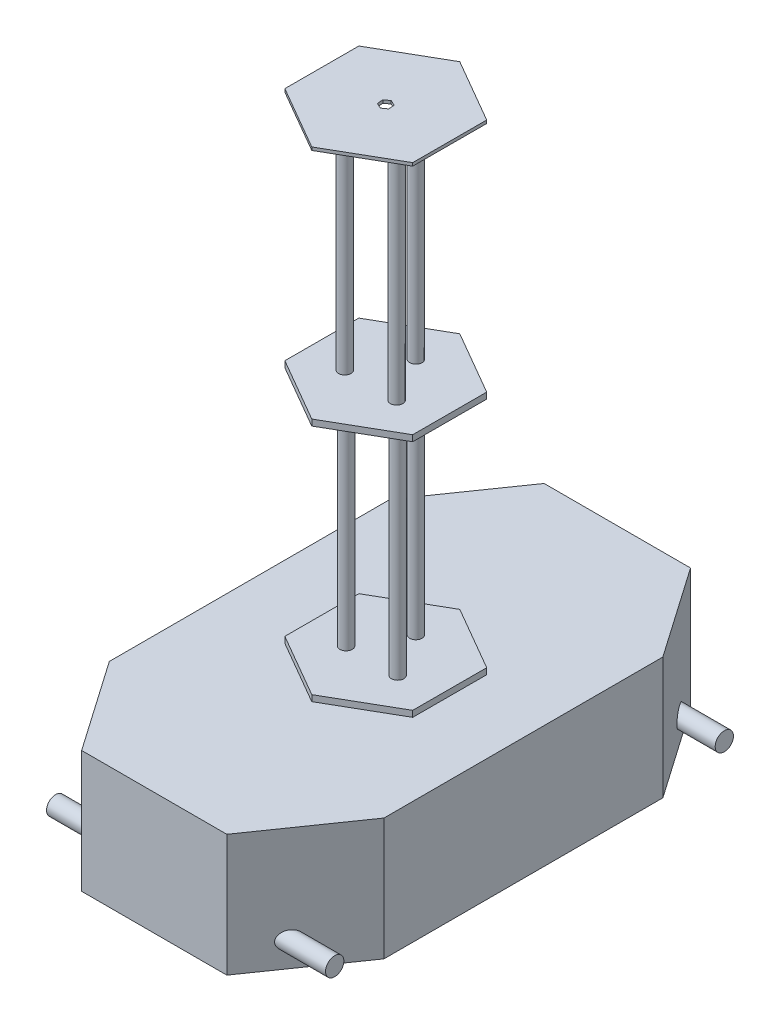
SolidWorks part; units mm, degrees
ref_plane "Front Plane" through (0, 0, 0) normal (0, 0, 1) x (1, 0, 0)
ref_plane "Top Plane" through (0, 0, 0) normal (0, 1, 0) x (1, 0, 0)
ref_plane "Right Plane" through (0, 0, 0) normal (1, 0, 0) x (0, 0, -1)
sketch "Sketch1" plane through (0, 0, 0) normal (0, 1, 0) x (1, 0, 0)
  line L0 (-1.4839, 377.6504) -> (238.5161, 377.6504)
  line L1 (-1.4839, 377.6504) -> (238.5161, 377.6504)
  line L2 (-105.1951, 228.5791) -> (-105.1951, -231.4209)
  line L3 (-1.4839, -380.4923) -> (236.539, -380.4923)
  line L4 (342.2273, 228.5791) -> (342.2273, -228.5791)
  line L12 (342.2273, 228.5791) -> (342.2273, -228.5791)
  line L14 (-1.4839, 377.6504) -> (-105.1951, 228.5791)
  line L15 (238.5161, 377.6504) -> (342.2273, 228.5791)
  line L16 (342.2273, -228.5791) -> (236.539, -380.4923)
  line L17 (-1.4839, -380.4923) -> (-105.1951, -231.4209)
  line L18 (-1.4839, 377.6504) -> (238.5161, 377.6504)
  point P0 (0, 0)
  point P1 (0, 0)
  point P2 (0, 0)
  point P9 (118.5161, 377.6504)
  point P12 (0, 0)
  dimension "D1" = 240
  dimension "D2" = 460
  dimension "D3" = 447.4224
  dimension "D4" = 758.1427
extrude "Boss-Extrude1" add sketch "Sketch1" along normal blind 200 contours L17 L3 L16 L4 L15 L0 L14 L2
sketch "Sketch2" plane through (0, 200, 0) normal (0, 1, 0) x (1, 0, 0)
  line L0 (118.5161, 377.6504) -> (117.5275, -380.4923)
  line L1 (-1.4839, 377.6504) -> (238.5161, 377.6504) construction
  line L2 (-1.4839, -380.4923) -> (236.539, -380.4923) construction
  line L3 (-105.1951, -1.4209) -> (342.2273, 0)
  line L4 (-105.1951, 228.5791) -> (-105.1951, -231.4209) construction
  line L5 (342.2273, 228.5791) -> (342.2273, -228.5791) construction
  line L8 (128.0198, -1.434) -> (128.0208, -0.6803)
  line L11 (108.0246, -0.7438) -> (108.0237, -1.4079)
  line L13 (196.0959, 55.0556) -> (154.3396, 31.0202) [skipped]
  line L14 (205.969, -40.7968) -> (164.2755, -16.6525) [skipped]
  line L15 (39.9477, -57.8975) -> (81.704, -33.862) [skipped]
  line L16 (30.0746, 37.955) -> (71.7681, 13.8107) [skipped]
  line L17 (117.9013, -93.7969) -> (197.9615, -47.7132)
  line L18 (197.9615, -47.7132) -> (198.0819, 44.6627)
  line L19 (198.0819, 44.6627) -> (118.1422, 90.955)
  line L20 (118.1422, 90.955) -> (38.0821, 44.8714)
  line L21 (38.0821, 44.8714) -> (37.9616, -47.5046)
  line L22 (37.9616, -47.5046) -> (117.9013, -93.7969)
  line L23 (117.8638, -122.5905) -> (222.8787, -62.1425)
  line L24 (222.8787, -62.1425) -> (223.0367, 59.027)
  line L25 (223.0367, 59.027) -> (118.1798, 119.7486)
  line L26 (118.1798, 119.7486) -> (13.1649, 59.3007)
  line L27 (13.1649, 59.3007) -> (13.0069, -61.8689)
  line L28 (13.0069, -61.8689) -> (117.8638, -122.5905)
  arc A0 (108.0467, -0.7437) -> (108.0237, -1.4079) centre (118.0218, -1.4209) ccw construction
  arc A1 (128.0198, -1.434) -> (108.0467, -0.7437) centre (118.0218, -1.4209) ccw construction
  circle A2 centre (118.0218, -1.4209) radius 80 construction
  circle A3 centre (118.0218, -1.4209) radius 104.936 construction
  circle A4 centre (118.0218, -1.4209) radius 80
  circle A5 centre (118.0218, -1.4209) radius 40
extrude "Boss-Extrude2" add sketch "Sketch2" along normal blind 10 contours L27 L28 L0 L22 L21 L3 | L26 L27 L3 L21 L20 L0 | L24 L25 L0 L19 L18 L3 | L23 L24 L3 L18 L17 L0 | A5 L3 A4 L0 | A4 L3 L18 L19 | A4 L19 L0 | A4 L0 L20 | A4 L20 L21 L3 | A5 L0 A4 L3 | A5 L3 A4 L0 | A5 L0 A4 L3 | A4 L17 L18 | A4 L0 L17 | A4 L22 L0 | A4 L21 L22
sketch "Sketch3" plane through (0, 210, 0) normal (0, 1, 0) x (1, 0, 0)
  line L0 (118.1798, 119.7486) -> (118.1798, 47.7486)
  line L1 (-105.1951, -1.4209) -> (342.2273, 0)
  line L2 (-105.1951, 228.5791) -> (-105.1951, -231.4209) construction
  line L3 (342.2273, 228.5791) -> (342.2273, -228.5791) construction
  line L4 (117.8638, -122.5905) -> (118.1798, 119.7486)
  line L5 (13.291, 60.7944) -> (223.0048, -60.6488)
  line L6 (224.3934, 59.6647) -> (14.3636, -61.2312)
  circle A0 centre (118.1798, 47.7486) radius 10.16
  circle A1 centre (160.651, -24.6488) radius 10.16
  circle A2 centre (76.7174, -25.2312) radius 10.16
  point P22 (118.5161, -0.7105)
  dimension "D1" = 3
  dimension "D3" = 20.32
  dimension "D2" = 72
extrude "Boss-Extrude3" add sketch "Sketch3" along normal blind 381.28 separate body
ref_plane "Plane1" through (0, 591.28, 0) normal (0, 1, 0) x (1, 0, 0)
sketch "Sketch4" plane through (0, 591.28, 0) normal (0, 1, 0) x (1, 0, 0)
  line L0 (118.1798, 119.7486) -> (117.8638, -122.5905)
  line L2 (222.8787, -62.1425) -> (223.0367, 59.027)
  line L3 (223.0367, 59.027) -> (118.1798, 119.7486)
  line L4 (118.1798, 119.7486) -> (13.1649, 59.3007)
  line L5 (13.1649, 59.3007) -> (13.0069, -61.8689)
  line L6 (13.0069, -61.8689) -> (117.8638, -122.5905)
  line L7 (117.8638, -122.5905) -> (222.8787, -62.1425)
  line L8 (198.8044, -46.226) -> (197.2155, 46.1364)
  line L9 (197.2155, 46.1364) -> (116.4328, 90.9415)
  line L10 (116.4328, 90.9415) -> (37.2391, 43.3842)
  line L11 (37.2391, 43.3842) -> (38.8281, -48.9782)
  line L12 (38.8281, -48.9782) -> (119.6108, -93.7833)
  line L13 (119.6108, -93.7833) -> (198.8044, -46.226)
  circle A0 centre (118.0218, -1.4209) radius 104.936 construction
  circle A1 centre (118.0218, -1.4209) radius 80 construction
extrude "Boss-Extrude4" add sketch "Sketch4" along normal blind 10 separate body contours L12 L13 L8 L9 L0 | L12 L11 L10 L9 L0 L4 L5 L6 | L11 L12 L0 L9 L10 | L13 L12 L0 L7 L2 L3 L9 L8
sketch "Sketch6" plane through (0, 601.28, 0) normal (0, 1, 0) x (1, 0, 0)
  line L0 (118.1798, 119.7486) -> (118.1798, 47.7486)
  line L1 (13.0859, -1.2841) -> (222.9577, -1.5577)
  line L2 (13.1649, 59.3007) -> (13.0069, -61.8689) construction
  line L3 (222.8787, -62.1425) -> (223.0367, 59.027) construction
  circle A0 centre (118.1798, 47.7486) radius 10.16
  circle A1 centre (160.5249, -26.1425) radius 10.16
  circle A2 centre (75.3607, -25.8689) radius 10.16
  point P10 (0, 0)
  point P17 (118.0218, -1.4209)
  dimension "D1" = 3
extrude "Boss-Extrude5" add sketch "Sketch6" along normal blind 381.28
ref_plane "Plane2" through (0, 982.56, 0) normal (0, 1, 0) x (1, 0, 0)
sketch "Sketch7" plane through (0, 982.56, 0) normal (0, 1, 0) x (1, 0, 0)
  line L0 (118.1798, 119.7486) -> (117.8638, -122.5905)
  line L1 (13.0859, -1.2841) -> (222.9577, -1.5577)
  line L2 (13.1649, 59.3007) -> (13.0069, -61.8689) construction
  line L3 (222.8787, -62.1425) -> (223.0367, 59.027) construction
  line L5 (222.8787, -62.1425) -> (223.0367, 59.027)
  line L6 (223.0367, 59.027) -> (118.1798, 119.7486)
  line L7 (118.1798, 119.7486) -> (13.1649, 59.3007)
  line L8 (13.1649, 59.3007) -> (13.0069, -61.8689)
  line L9 (13.0069, -61.8689) -> (117.8638, -122.5905)
  line L10 (117.8638, -122.5905) -> (222.8787, -62.1425)
  line L11 (126.9308, -5.5394) -> (126.043, 4.2353)
  line L12 (126.043, 4.2353) -> (117.134, 8.3538)
  line L13 (117.134, 8.3538) -> (109.1127, 2.6976)
  line L14 (109.1127, 2.6976) -> (110.0005, -7.0771)
  line L15 (110.0005, -7.0771) -> (118.9096, -11.1956)
  line L16 (118.9096, -11.1956) -> (126.9308, -5.5394)
  line L17 (117.9013, -93.7969) -> (197.9615, -47.7132)
  line L18 (197.9615, -47.7132) -> (198.0819, 44.6627)
  line L19 (198.0819, 44.6627) -> (118.1422, 90.955)
  line L20 (118.1422, 90.955) -> (38.0821, 44.8714)
  line L21 (38.0821, 44.8714) -> (37.9616, -47.5046)
  line L22 (37.9616, -47.5046) -> (117.9013, -93.7969)
  circle A0 centre (118.0218, -1.4209) radius 104.936 construction
  circle A1 centre (118.0218, -1.4209) radius 8.5 construction
  circle A2 centre (118.0218, -1.4209) radius 80 construction
extrude "Boss-Extrude6" add sketch "Sketch7" along normal blind 5 contours L21 L22 L0 L15 L14 L1 | L20 L21 L1 L14 L13 L12 L0 | L21 L20 L0 L7 L8 L1 | L22 L21 L1 L8 L9 L0 | L17 L18 L1 L11 L16 L15 L0 | L18 L17 L0 L10 L5 L1 | L18 L19 L0 L12 L11 L1 | L19 L18 L1 L5 L6 L0
sketch "Sketch8" plane through (342.2273, 0, 39.3094) normal (-1, 0, 0) x (0, 0, 1)
  line L0 (-416.9598, 200) -> (-416.9598, 0) construction
  line L2 (-416.9598, 0) -> (-267.8885, 0) construction
  circle A0 centre (-326.1598, 40) radius 15
  dimension "D1" = 90.8
  dimension "D3" = 30
  dimension "D2" = 40
extrude "Boss-Extrude7" [suppressed] add sketch "Sketch8" along normal blind 65
ref_plane "Plane7" through (118.5173, 0, 0) normal (1, 0, 0) x (0, 0, -1)
sketch "Sketch9" plane through (337.7672, 0, 234.9898) normal (0.8209, 0, 0.5711) x (0.5711, 0, -0.8209)
  line L0 (-177.2516, 200) -> (-177.2516, 0) construction
  line L1 (254.9814, 0) -> (-254.9814, 0) construction
  circle A0 centre (-86.4516, 40) radius 15
  point P4 (0, 0)
  dimension "D3" = 30
  dimension "D1" = 90.8
  dimension "D2" = 40
extrude "Boss-Extrude8" [suppressed] add sketch "Sketch9" along normal blind 65
mirror "Mirror4" [suppressed] about plane through (118.5173, 0, 0) normal (1, 0, 0)
ref_plane "Plane8" through (352.2273, 0, 0) normal (1, 0, 0) x (0, 0, -1)
sketch "Sketch11" plane through (352.2273, 0, 0) normal (1, 0, 0) x (0, 0, -1)
  line L0 (246.0823, 0) -> (-246.0823, 0) construction
  line L1 (-228.5791, 200) -> (-228.5791, 0) construction
  circle A0 centre (-319.3791, 40) radius 15
  point P6 (0, 0)
  point P7 (0, 0)
  dimension "D1" = 40
  dimension "D2" = 90.8
extrude "Boss-Extrude9" add sketch "Sketch11" against normal through all contours A0
mirror "Mirror6" about plane through (0, 0, 0) normal (0, 0, 1) of "Boss-Extrude9"
